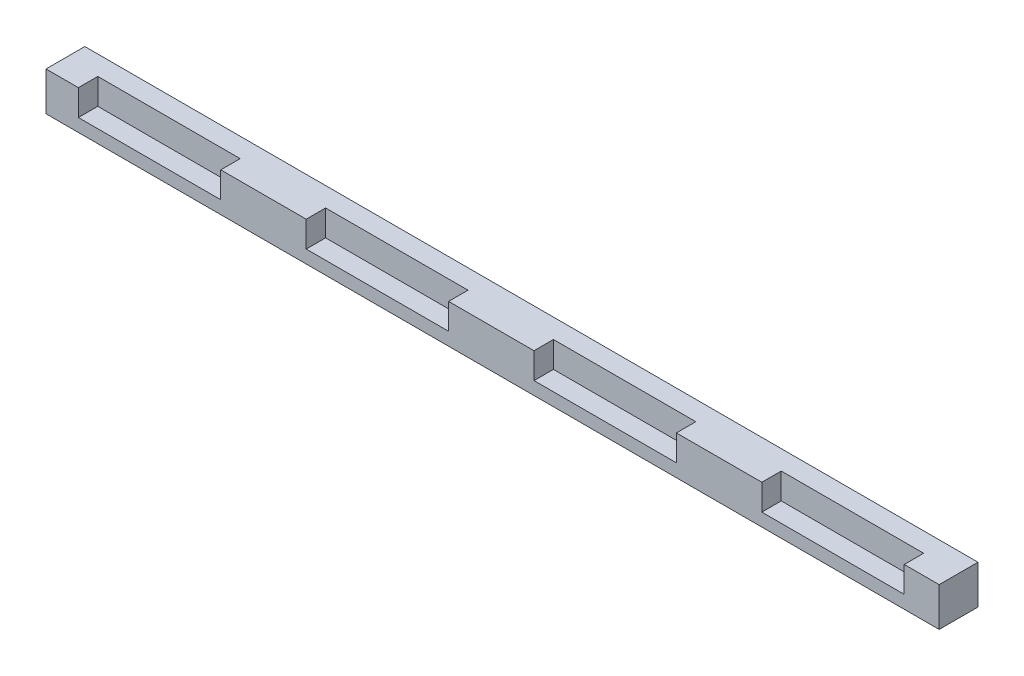
SolidWorks part; units mm, degrees
material "AISI 1035 Сталь (SS)"
ref_plane "Спереди" through (0, 0, 0) normal (0, 0, 1) x (1, 0, 0)
ref_plane "Сверху" through (0, 0, 0) normal (0, 1, 0) x (1, 0, 0)
ref_plane "Справа" through (0, 0, 0) normal (1, 0, 0) x (0, 0, -1)
sketch "Эскиз1" plane through (0, 0, 0) normal (0, 0, 1) x (1, 0, 0)
  line L1 (44.0503, 37.6311) -> (734.0503, 37.6311)
  line L2 (44.0503, 37.6311) -> (44.0503, 7.6311)
  line L3 (44.0503, 7.6311) -> (734.0503, 7.6311)
  line L4 (734.0503, 37.6311) -> (734.0503, 7.6311)
  dimension "D1" = 690
  dimension "D2" = 30
extrude "Бобышка-Вытянуть1" add sketch "Эскиз1" along normal blind 30
sketch "Эскиз2" plane through (0, 37.6311, 0) normal (0, 1, 0) x (1, 0, 0)
  line L0 (734.0503, -30) -> (44.0503, -30) construction
  line L1 (69.0503, -30) -> (179.0503, -30)
  line L2 (69.0503, -30) -> (69.0503, -15)
  line L3 (69.0503, -15) -> (179.0503, -15)
  line L4 (179.0503, -30) -> (179.0503, -15)
  line L5 (44.0503, -30) -> (44.0503, 0) construction
  line L6 (734.0503, 0) -> (44.0503, 0) construction
  dimension "D1" = 25
  dimension "D2" = 15
  dimension "D3" = 110
extrude "Вырез-Вытянуть1" cut sketch "Эскиз2" against normal blind 20
pattern_linear "Линейный массив1" count 4 spacing 176 along (1, 0, 0) of "Вырез-Вытянуть1"
